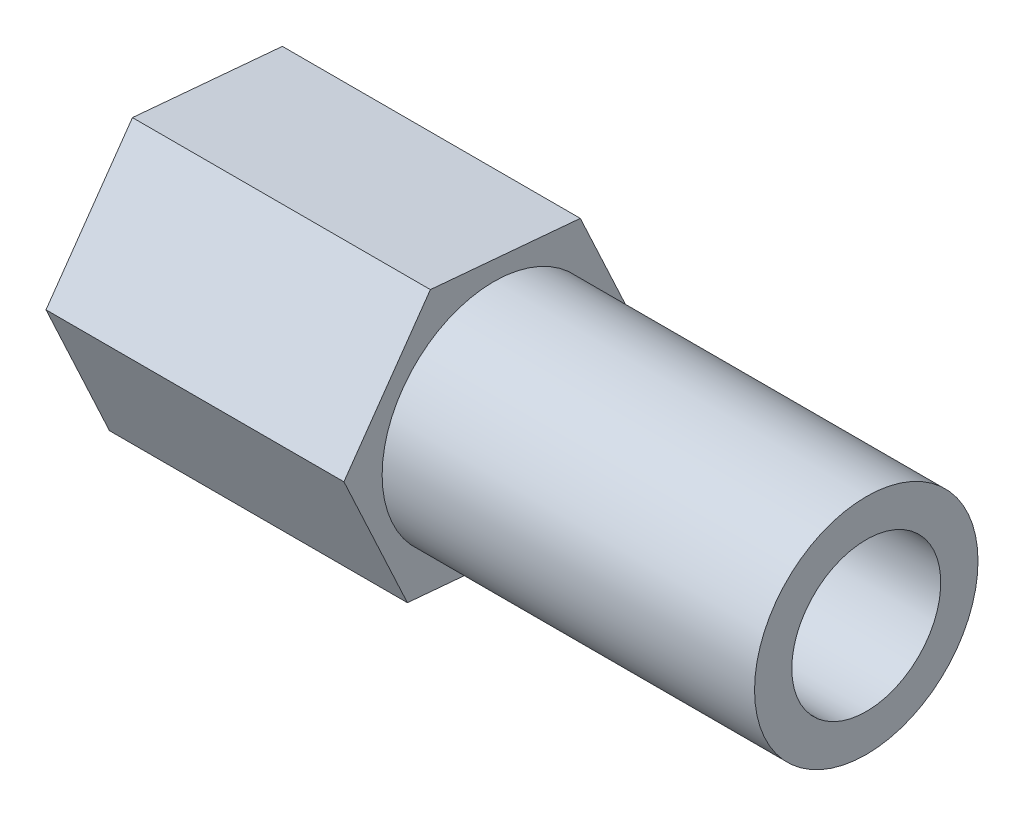
SolidWorks part; units mm, degrees
ref_plane "前视基准面" through (0, 0, 0) normal (0, 0, 1) x (1, 0, 0)
ref_plane "上视基准面" through (0, 0, 0) normal (0, 1, 0) x (1, 0, 0)
ref_plane "右视基准面" through (0, 0, 0) normal (1, 0, 0) x (0, 0, -1)
sketch "草图1" plane through (0, 0, 0) normal (1, 0, 0) x (0, 0, -1)
  line L1 (1.7044, -3.6645) -> (4.0257, -0.3561)
  line L2 (4.0257, -0.3561) -> (2.3213, 3.3083)
  line L3 (2.3213, 3.3083) -> (-1.7044, 3.6645)
  line L4 (-1.7044, 3.6645) -> (-4.0257, 0.3561)
  line L5 (-4.0257, 0.3561) -> (-2.3213, -3.3083)
  line L6 (-2.3213, -3.3083) -> (1.7044, -3.6645)
  circle A0 centre (0, 0) radius 3.5 construction
extrude "凸台-拉伸1" add sketch "草图1" along normal blind 8
sketch "草图2" plane through (8, 0, 0) normal (1, 0, 0) x (0, 0, -1)
  circle A0 centre (0, 0) radius 3
extrude "凸台-拉伸2" add sketch "草图2" along normal blind 10
sketch "草图3" plane through (0, 0, 0) normal (-1, 0, 0) x (0, 0, 1)
  circle A0 centre (0, 0) radius 2
extrude "切除-拉伸1" cut sketch "草图3" against normal through all
sketch "草图4" plane through (0, 0, 0) normal (0, 0, 1) x (1, 0, 0)
  line L0 (-1.8006, 0) -> (20.8131, 0) construction
  circle A0 centre (13.0783, 0) radius 1.5
extrude "切除-拉伸2" cut sketch "草图4" against normal blind 10
